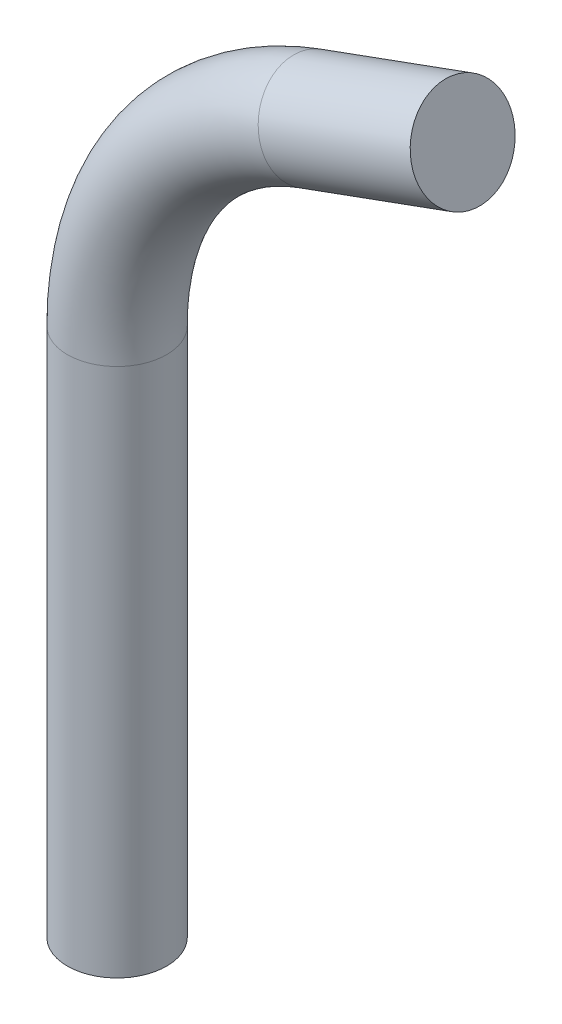
SolidWorks part; units mm, degrees
ref_plane "Front Plane" through (0, 0, 0) normal (0, 0, 1) x (1, 0, 0)
ref_plane "Top Plane" through (0, 0, 0) normal (0, 1, 0) x (1, 0, 0)
ref_plane "Right Plane" through (0, 0, 0) normal (1, 0, 0) x (0, 0, -1)
sketch "Sketch1" plane through (0, 0, 0) normal (0, 0, 1) x (1, 0, 0)
  line L0 (0, 0) -> (0, 71.9917)
  line L1 (26.3192, 109.5794) -> (46.9846, 117.101)
  arc A0 (0, 71.9917) -> (26.3192, 109.5794) centre (40, 71.9917) cw
  point P6 (0, 100)
  dimension "D3" = 40
  dimension "D1" = 50
  dimension "D2" = 100
  dimension "D4" = 110
sketch "Sketch2" plane through (0, 0, 0) normal (0, 1, 0) x (1, 0, 0)
  circle A0 centre (0, 0) radius 6.75
  dimension "D1" = 13.5
sweep "Sweep1" add profiles "Sketch2" path "Sketch1"
